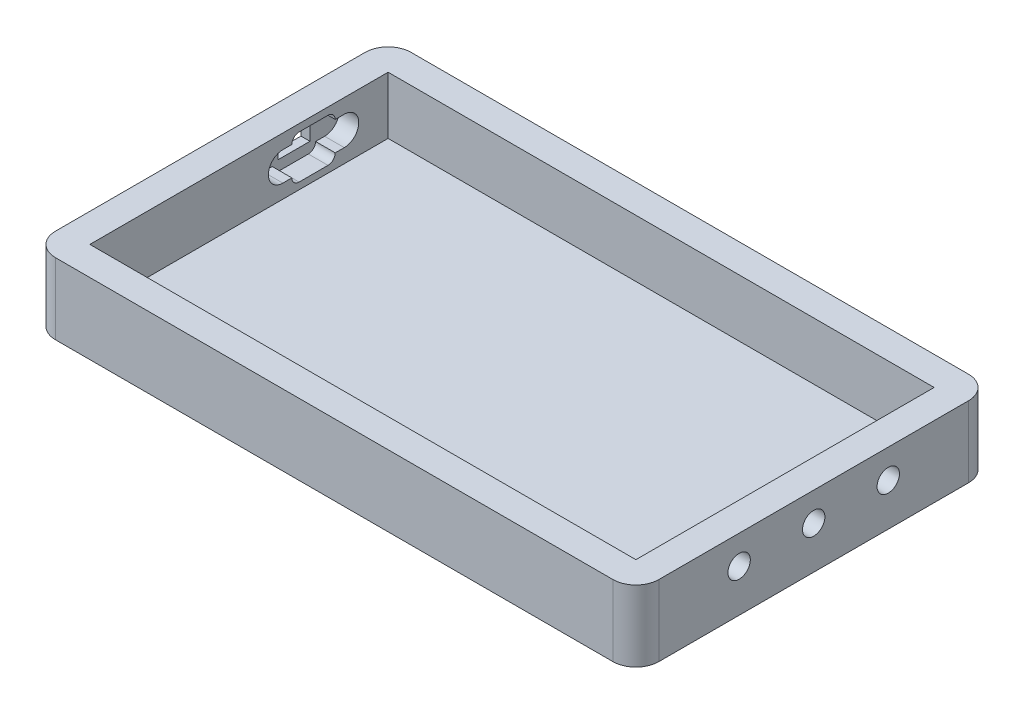
SolidWorks part; units mm, degrees
ref_plane "Front Plane" through (0, 0, 0) normal (0, 0, 1) x (1, 0, 0)
ref_plane "Top Plane" through (0, 0, 0) normal (0, 1, 0) x (1, 0, 0)
ref_plane "Right Plane" through (0, 0, 0) normal (1, 0, 0) x (0, 0, -1)
sketch "Sketch1" plane through (0, 0, 0) normal (0, 1, 0) x (1, 0, 0)
  line L0 (0, 0) -> (151.13, 0)
  line L1 (151.13, 0) -> (151.13, 82.55)
  line L2 (151.13, 82.55) -> (0, 82.55)
  line L3 (0, 82.55) -> (0, 0)
  line L5 (-7.9375, 82.55) -> (-7.9375, -7.9375)
  line L6 (-7.9375, -7.9375) -> (159.0675, -7.9375)
  line L7 (159.0675, -7.9375) -> (159.0675, 90.4875)
  line L8 (159.0675, 90.4875) -> (-7.9375, 90.4875)
  line L9 (-7.9375, 90.4875) -> (-7.9375, 82.55)
extrude "Boss-Extrude1" add sketch "Sketch1" along normal blind 15.875
sketch "Sketch2" plane through (0, 0, 0) normal (0, -1, 0) x (1, 0, 0)
  line L0 (159.0675, 7.9375) -> (159.0675, -90.4875)
  line L1 (159.0675, -90.4875) -> (-7.9375, -90.4875)
  line L2 (-7.9375, -90.4875) -> (-7.9375, 7.9375)
  line L3 (-7.9375, 7.9375) -> (159.0675, 7.9375)
extrude "Boss-Extrude2" add sketch "Sketch2" along normal blind 3.81
fillet "Fillet2" radius 6.35 4 edges at (159.0675, 6.0325, 7.9375) (-7.9375, 6.0325, 7.9375) (-7.9375, 6.0325, -90.4875) (159.0675, 6.0325, -90.4875)
sketch "Sketch3" plane through (151.13, 0, 0) normal (-1, 0, 0) x (0, 0, 1)
  line L0 (-82.55, 15.875) -> (0, 15.875)
  line L1 (0, 15.875) -> (0, 0)
  line L2 (0, 0) -> (-82.55, 0)
  line L3 (-82.55, 0) -> (-82.55, 15.875)
  line L4 (-41.275, 15.875) -> (-41.275, 0)
  line L5 (-41.275, 7.9375) -> (-82.55, 7.9375)
  line L6 (-41.275, 7.9375) -> (0, 7.9375)
  circle A0 centre (-61.9125, 7.9375) radius 3.0988
  circle A1 centre (-41.275, 7.9375) radius 3.0988
  circle A2 centre (-20.6375, 7.9375) radius 3.0988
extrude "Cut-Extrude1" cut sketch "Sketch3" against normal through all contours L5 A0 | L5 A0 | L5 A1 L4 | L4 A1 L5 | L6 A1 L4 | L4 A1 L6 | L6 A2 | L6 A2
sketch "Sketch4" plane through (0, 0, 0) normal (1, 0, 0) x (0, 0, -1)
  line L4 (57.9125, 13.8694) -> (65.9125, 13.8694)
  line L11 (67.9125, 11.8694) -> (70.4125, 11.8694)
  line L15 (70.4125, 3.8694) -> (67.9125, 3.8694)
  line L16 (65.9125, 1.8694) -> (57.9125, 1.8694)
  line L18 (53.4125, 3.8694) -> (55.9125, 3.8694)
  line L22 (55.9125, 11.8694) -> (53.4125, 11.8694)
  arc A0 (67.9125, 11.8694) -> (65.9125, 13.8694) centre (65.9125, 11.8694) ccw
  arc A1 (70.4125, 3.8694) -> (70.4125, 11.8694) centre (70.4125, 7.8694) ccw
  arc A2 (65.9125, 1.8694) -> (67.9125, 3.8694) centre (65.9125, 3.8694) ccw
  arc A4 (53.4125, 3.8694) -> (53.4125, 11.8694) centre (53.4125, 7.8694) cw
  arc A6 (55.9125, 11.8694) -> (57.9125, 13.8694) centre (57.9125, 11.8694) cw
  arc A7 (57.9125, 1.8694) -> (55.9125, 3.8694) centre (57.9125, 3.8694) cw
  point P9 (61.9125, 7.9375)
extrude "Cut-Extrude3" cut sketch "Sketch4" against normal blind 5.4356
sketch "Sketch5" plane through (-5.4356, 0, 0) normal (1, 0, 0) x (0, 0, -1)
  line L0 (57.9125, 1.8694) -> (65.9125, 1.8694)
  line L3 (57.4675, 4.6944) -> (66.3575, 4.6944)
  line L4 (57.4675, 4.6944) -> (57.4675, 11.0444)
  line L5 (57.4675, 11.0444) -> (66.3575, 11.0444)
  line L6 (66.3575, 4.6944) -> (66.3575, 11.0444)
extrude "Cut-Extrude4" cut sketch "Sketch5" against normal through all contours L3 L6 L5 L4
